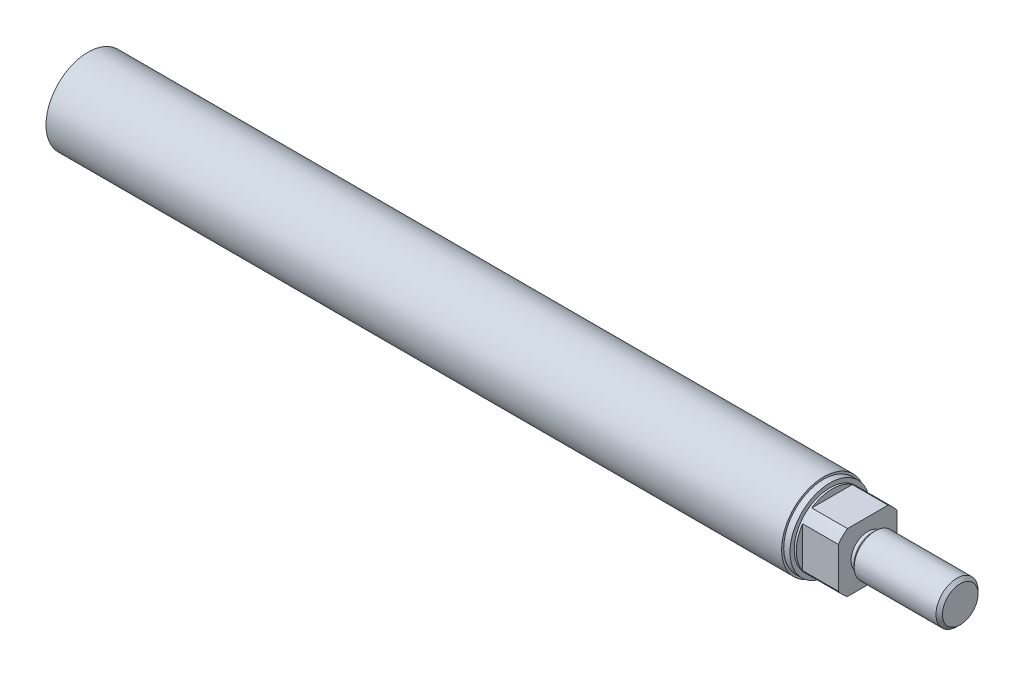
SolidWorks part; units mm, degrees
ref_plane "Front Plane" through (0, 0, 0) normal (0, 0, 1) x (1, 0, 0)
ref_plane "Top Plane" through (0, 0, 0) normal (0, 1, 0) x (1, 0, 0)
ref_plane "Right Plane" through (0, 0, 0) normal (1, 0, 0) x (0, 0, -1)
ref_plane "Plane1" through (0, 0, 0) normal (0, 0, 1) x (1, 0, 0)
sketch "Sketch1" plane through (0, 0, 0) normal (0, 0, 1) x (1, 0, 0)
  line L0 (-165, 0) -> (-165, 10)
  line L1 (-165, 10) -> (10, 10)
  line L2 (10, 10) -> (10, 9.5)
  line L3 (10, 9.5) -> (11.5, 9.5)
  line L4 (11.5, 9.5) -> (11.5, 8.5)
  line L5 (11.5, 8.5) -> (20.5, 8.5)
  line L6 (20.5, 8.5) -> (20.5, 4)
  line L7 (20.5, 4) -> (21.5, 4)
  line L8 (21.5, 4) -> (21.5, 4.233)
  line L9 (21.5, 4.233) -> (22.267, 5)
  line L10 (22.267, 5) -> (41.733, 5)
  line L11 (41.733, 5) -> (42.5, 4.233)
  line L12 (42.5, 4.233) -> (42.5, 0)
  line L13 (42.5, 0) -> (-165, 0)
  line L14 (42.5, 0) -> (-165, 0) construction
revolve "Revolve1" add sketch "Sketch1" angle 360 about L14
ref_plane "Plane2" through (20.5, 0, 0) normal (1, 0, 0) x (0, 0, -1)
sketch "Sketch2" plane through (20.5, 0, 0) normal (1, 0, 0) x (0, 0, -1)
  line L0 (-7, 7) -> (-7, -7)
  line L1 (-7, -7) -> (7, -7)
  line L2 (7, -7) -> (7, 7)
  line L3 (7, 7) -> (-7, 7)
  circle A0 centre (0, 0) radius 11
extrude "Cut-Extrude1" cut sketch "Sketch2" against normal blind 8.5
